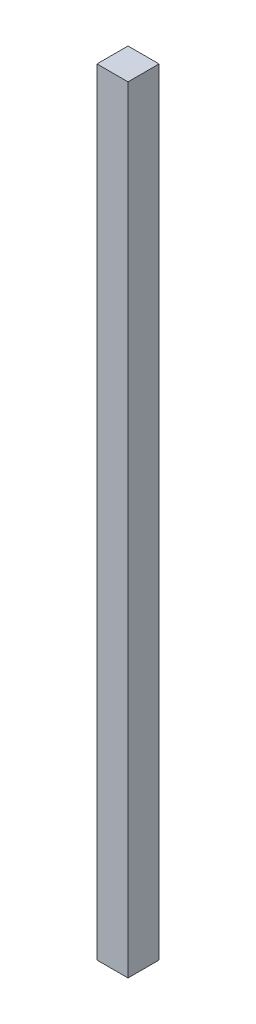
SolidWorks part; units mm, degrees
ref_plane "Front Plane" through (0, 0, 0) normal (0, 0, 1) x (1, 0, 0)
ref_plane "Top Plane" through (0, 0, 0) normal (0, 1, 0) x (1, 0, 0)
ref_plane "Right Plane" through (0, 0, 0) normal (1, 0, 0) x (0, 0, -1)
sketch "Sketch1" plane through (0, 0, 0) normal (0, 1, 0) x (1, 0, 0)
  line L1 (-10, 10) -> (10, 10)
  line L2 (-10, 10) -> (-10, -10)
  line L3 (-10, -10) -> (10, -10)
  line L4 (10, 10) -> (10, -10)
  line L5 (-10, 10) -> (10, -10) construction
  line L6 (-10, -10) -> (10, 10) construction
  point P0 (0, 0)
  dimension "D1" = 20
  dimension "D2" = 20
extrude "Boss-Extrude1" add sketch "Sketch1" along normal blind 500
